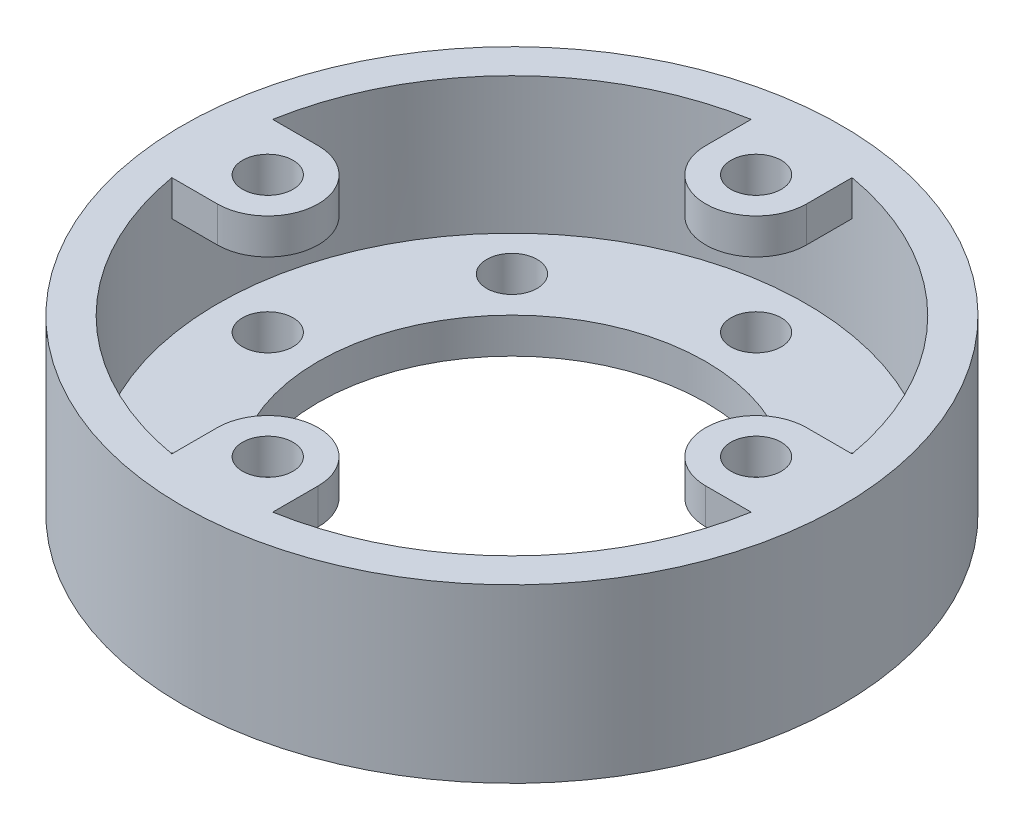
SolidWorks part; units mm, degrees
ref_plane "Front Plane" through (0, 0, 0) normal (0, 0, 1) x (1, 0, 0)
ref_plane "Top Plane" through (0, 0, 0) normal (0, 1, 0) x (1, 0, 0)
ref_plane "Right Plane" through (0, 0, 0) normal (1, 0, 0) x (0, 0, -1)
sketch "Sketch11" plane through (0, 0, 0) normal (0, 1, 0) x (1, 0, 0)
  circle A0 centre (0, 0) radius 73.025
  circle A1 centre (0, 0) radius 42.926
  circle A3 centre (0, -54.102) radius 5.588
  circle A4 centre (-38.2559, -38.2559) radius 5.588
  circle A5 centre (-54.102, 0) radius 5.588
  circle A6 centre (-38.2559, 38.2559) radius 5.588
  circle A7 centre (0, 54.102) radius 5.588
  circle A8 centre (38.2559, 38.2559) radius 5.588
  circle A9 centre (54.102, 0) radius 5.588
  circle A10 centre (38.2559, -38.2559) radius 5.588
  point P23 (0, 0)
  dimension "D1" = 146.05
  dimension "D2" = 85.852
  dimension "D3" = 11.176
  dimension "D4" = 54.102
  dimension "D5" = 8
extrude "Boss-Extrude3" add sketch "Sketch11" along normal blind 7.874
sketch "Sketch12" plane through (0, 7.874, 0) normal (0, 1, 0) x (1, 0, 0)
  circle A0 centre (0, 0) radius 73.025
  circle A2 centre (0, 0) radius 65.151
  dimension "D1" = 146.05
  dimension "D2" = 7.874
extrude "Boss-Extrude4" add sketch "Sketch12" along normal blind 30.226
ref_plane "Plane2" through (0, 38.1, 0) normal (0, 1, 0) x (1, 0, 0)
sketch "Sketch19" plane through (0, 38.1, 0) normal (0, 1, 0) x (1, 0, 0)
  line L0 (-11.176, -54.102) -> (-11.176, -72.1647)
  line L1 (-11.176, -72.1647) -> (11.176, -72.1647)
  line L2 (11.176, -72.1647) -> (11.176, -54.102)
  line L3 (-54.102, 11.176) -> (-72.1647, 11.176)
  line L4 (-72.1647, -11.176) -> (-54.102, -11.176)
  line L5 (-72.1647, 11.176) -> (-72.1647, -11.176)
  line L6 (11.176, 54.102) -> (11.176, 72.1647)
  line L7 (-11.176, 72.1647) -> (-11.176, 54.102)
  line L8 (11.176, 72.1647) -> (-11.176, 72.1647)
  line L9 (54.102, -11.176) -> (72.1647, -11.176)
  line L10 (72.1647, 11.176) -> (54.102, 11.176)
  line L11 (72.1647, -11.176) -> (72.1647, 11.176)
  circle A0 centre (0, -54.102) radius 5.588
  arc A1 (11.176, -54.102) -> (-11.176, -54.102) centre (0, -54.102) ccw
  circle A2 centre (0, -54.102) radius 5.588 construction
  circle A3 centre (0, 0) radius 73.025 construction
  arc A4 (-54.102, -11.176) -> (-54.102, 11.176) centre (-54.102, 0) ccw
  circle A5 centre (-54.102, 0) radius 5.588
  arc A6 (-11.176, 54.102) -> (11.176, 54.102) centre (0, 54.102) ccw
  circle A7 centre (0, 54.102) radius 5.588
  arc A8 (54.102, 11.176) -> (54.102, -11.176) centre (54.102, 0) ccw
  circle A9 centre (54.102, 0) radius 5.588
  point P32 (0, 0)
  dimension "D1" = 22.352
  dimension "D2" = 4
extrude "Boss-Extrude5" add sketch "Sketch19" against normal blind 7.874
